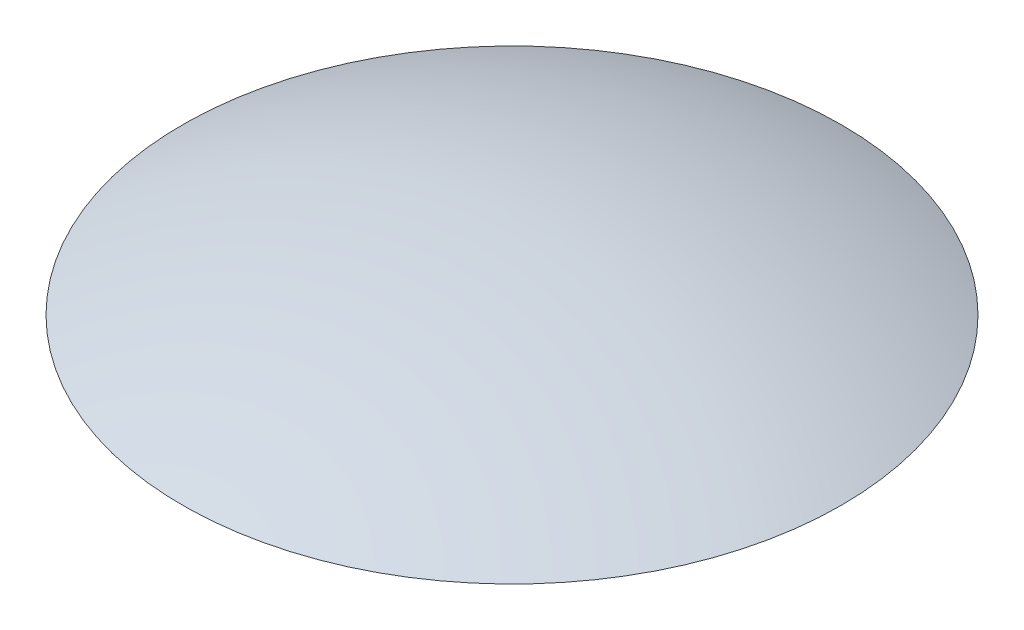
SolidWorks part; units mm, degrees
ref_plane "前视基准面" through (0, 0, 0) normal (0, 0, 1) x (1, 0, 0)
ref_plane "上视基准面" through (0, 0, 0) normal (0, 1, 0) x (1, 0, 0)
ref_plane "右视基准面" through (0, 0, 0) normal (1, 0, 0) x (0, 0, -1)
other "Configuration Table"
sketch "草图1" plane through (0, 0, 0) normal (0, 0, 1) x (1, 0, 0)
  line L0 (0, 0) -> (0, 31.0863) construction
  line L1 (4.0497, 15.2722) -> (7, 15.2722)
  line L2 (0, 16.8) -> (0, 15.8)
  arc A0 (7, 15.2722) -> (0, 16.8) centre (0, 0) ccw
  arc A1 (4.0497, 15.2722) -> (0, 15.8) centre (0, 0) ccw
  dimension "D1" = 33.6
  dimension "D3" = 31.6
  dimension "D2" = 14
revolve "旋转1" add sketch "草图1" angle 360 about L0
